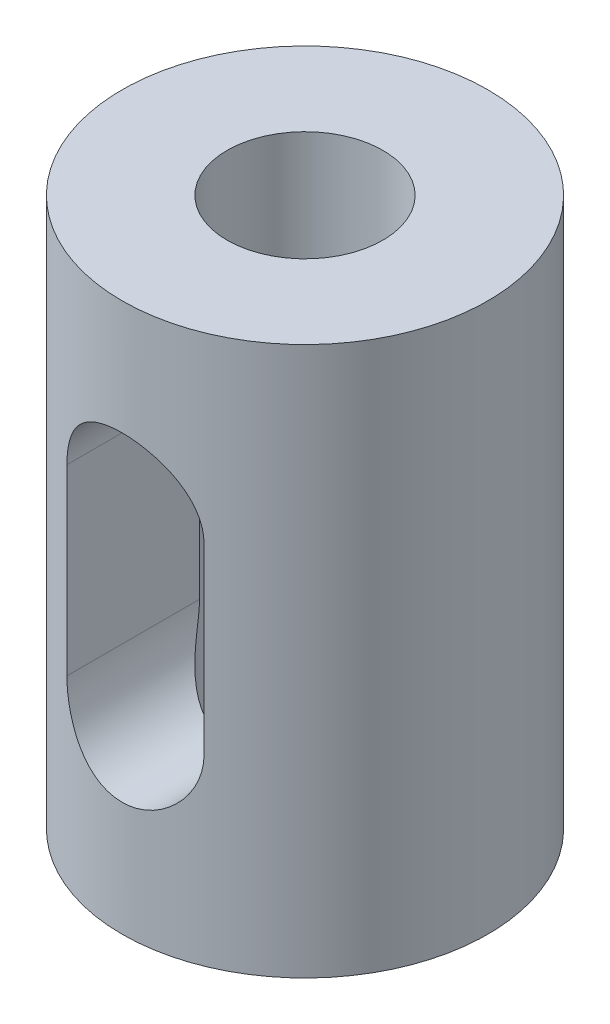
SolidWorks part; units mm, degrees
material "Titanium"
ref_plane "Front Plane" through (0, 0, 0) normal (0, 0, 1) x (1, 0, 0)
ref_plane "Top Plane" through (0, 0, 0) normal (0, 1, 0) x (1, 0, 0)
ref_plane "Right Plane" through (0, 0, 0) normal (1, 0, 0) x (0, 0, -1)
sketch "Sketch1" plane through (0, 0, 0) normal (0, 1, 0) x (1, 0, 0)
  circle A0 centre (0, 0) radius 3.175
  dimension "D1" = 6.35
extrude "Boss-Extrude1" add sketch "Sketch1" along normal blind 9.525
hole_wizard "Tap Drill for #6-32 Tap1" positions "Sketch3" profile "Sketch2" hole size "#6-32" standard "ANSI Inch" end condition through all
sketch "Sketch3" plane through (0, 9.525, 0) normal (0, 1, 0) x (1, 0, 0)
  point P0 (0, 0)
sketch "Sketch2" plane through (0, 9.525, 0) normal (1, 0, 0) x (0, 0, 1)
  line L0 (0, 0) -> (0, 9.525)
  line L1 (0, 9.525) -> (1.3525, 9.525)
  line L2 (1.3525, 9.525) -> (1.3525, 0)
  line L5 (1.3525, 0) -> (0, 0)
  line L11 (0, -6.35) -> (0, 107.95) construction
  dimension "Thru Hole Dia." = 2.7051
  dimension "Thru Hole Depth" = 9.525
cosmetic thread "Cosmetic Thread1" parameters "D2"=3.5052
cosmetic thread "Cosmetic Thread2" parameters "D2"=3.5052
sketch "Sketch4" plane through (0, 0, 0) normal (0, 0, 1) x (1, 0, 0)
  line L0 (0, 6.35) -> (0, 3.175) construction
  line L1 (1.1906, 6.35) -> (1.1906, 3.175)
  line L2 (-1.1906, 6.35) -> (-1.1906, 3.175)
  line L3 (-3.175, 0) -> (3.175, 0) construction
  line L4 (3.175, 9.525) -> (-3.175, 9.525) construction
  arc A0 (1.1906, 6.35) -> (-1.1906, 6.35) centre (0, 6.35) ccw
  arc A1 (-1.1906, 3.175) -> (1.1906, 3.175) centre (0, 3.175) ccw
  point P3 (0, 4.7625)
  dimension "D1" = 2.3813
  dimension "D2" = 3.175
  dimension "D3" = 3.175
extrude "Cut-Extrude1" cut sketch "Sketch4" against normal through all both and the other way through all
